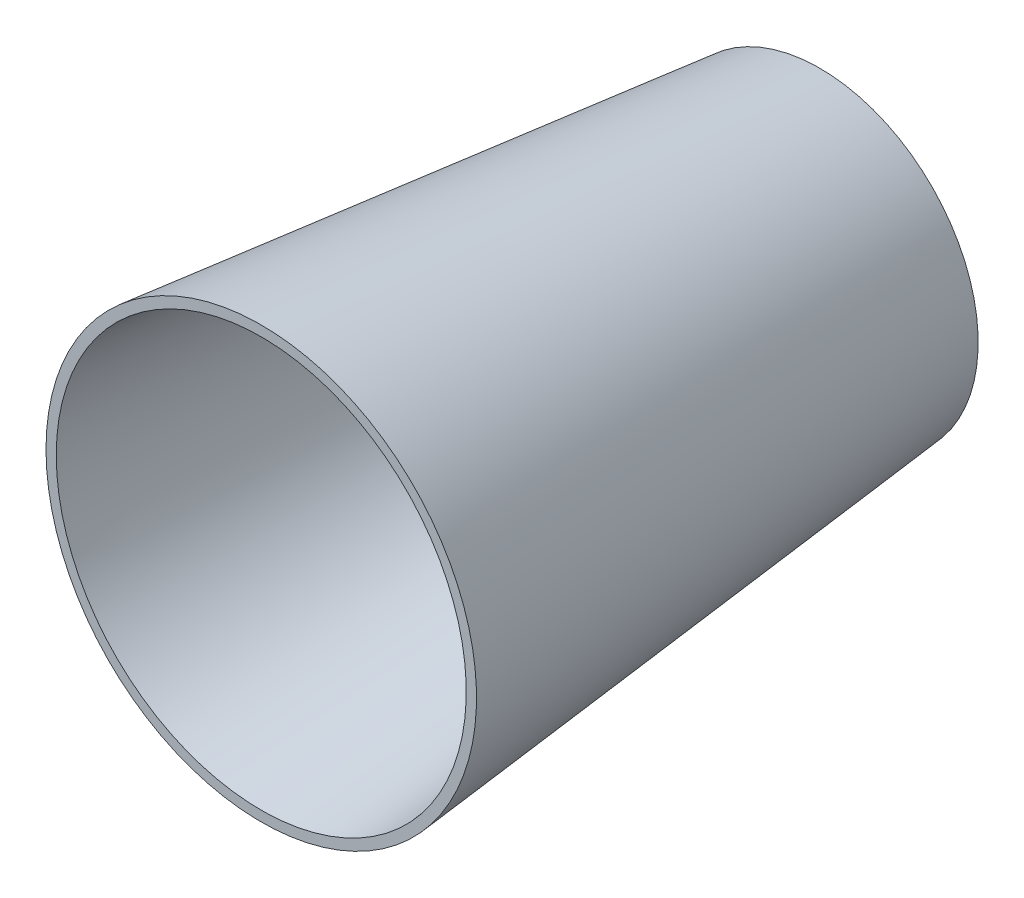
SolidWorks part; units mm, degrees
ref_plane "Front Plane" through (0, 0, 0) normal (0, 0, 1) x (1, 0, 0)
ref_plane "Top Plane" through (0, 0, 0) normal (0, 1, 0) x (1, 0, 0)
ref_plane "Right Plane" through (0, 0, 0) normal (1, 0, 0) x (0, 0, -1)
sketch "Sketch2" plane through (0, 0, 0) normal (1, 0, 0) x (0, 0, -1)
  line L4 (-33.8783, 481.3354) -> (-34.1217, 481.3354)
  line L5 (-34.1217, 481.3354) -> (-34.1217, 512.8354)
  line L6 (-34.1217, 512.8354) -> (47.6217, 504.4993)
  line L7 (47.6217, 504.4993) -> (47.6217, 481.4993)
  line L8 (47.6217, 481.4993) -> (46.1217, 481.3354)
  line L10 (46.1217, 481.3354) -> (-33.8783, 481.3354)
  point P5 (46.1217, 492.1673)
  dimension "D1" = 31.5
  dimension "D2" = 23
  dimension "D3" = 80
revolve "Revolve1" add sketch "Sketch2" angle 360 about L10
sketch "Sketch3" plane through (0, 0, 0) normal (1, 0, 0) x (0, 0, -1)
  line L0 (-34.1217, 511.3354) -> (46.1307, 503.1777)
  line L1 (-34.1217, 481.3354) -> (-34.1217, 512.8354) construction
  line L2 (46.1307, 503.1777) -> (46.1307, 481.3354)
  line L3 (46.1217, 481.3354) -> (-33.8783, 481.3354) construction
  line L6 (-34.1217, 511.3354) -> (-34.1217, 481.3354)
  line L7 (-34.1217, 481.3354) -> (46.1307, 481.3354)
  dimension "D1" = 1.5
  dimension "D2" = 1.5
revolve "Cut-Revolve1" cut sketch "Sketch3" angle 360 about L10
